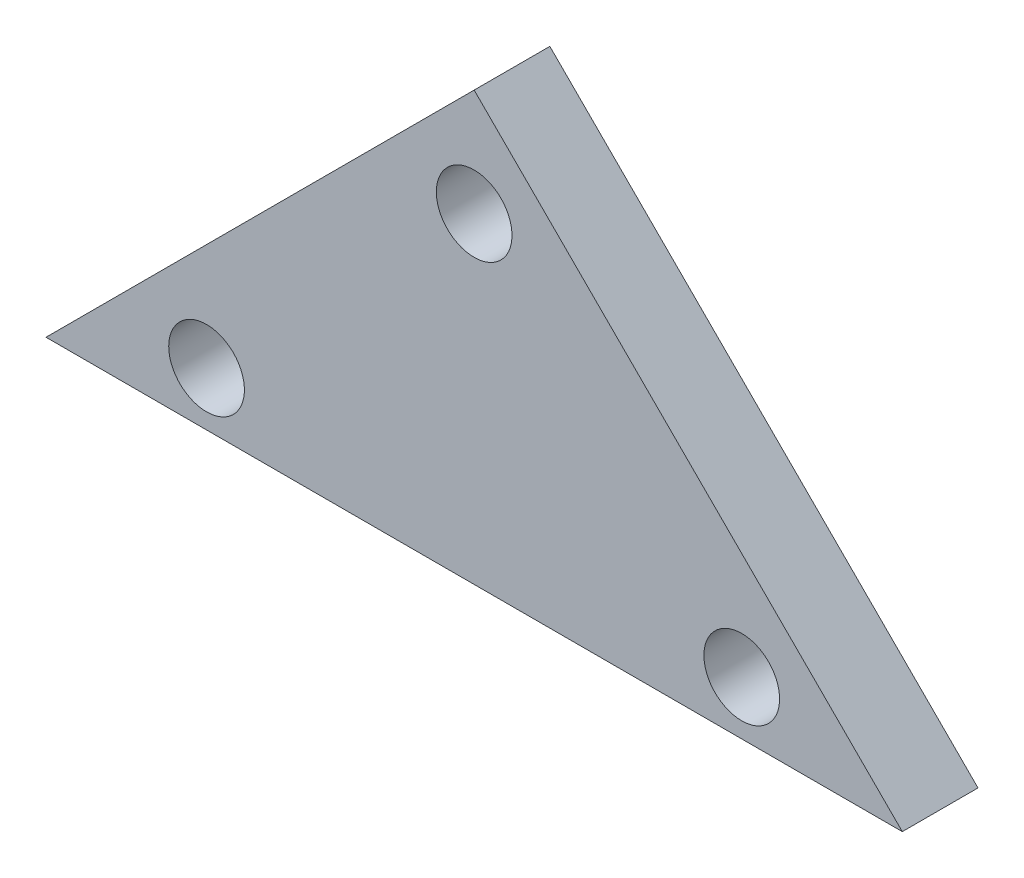
SolidWorks part; units mm, degrees
ref_plane "Front Plane" through (0, 0, 0) normal (0, 0, 1) x (1, 0, 0)
ref_plane "Top Plane" through (0, 0, 0) normal (0, 1, 0) x (1, 0, 0)
ref_plane "Right Plane" through (0, 0, 0) normal (1, 0, 0) x (0, 0, -1)
sketch "Sketch1" plane through (0, 0, 0) normal (0, 0, 1) x (1, 0, 0)
  line L0 (-26.9408, -20.2056) -> (26.9408, -20.2056)
  line L1 (26.9408, -20.2056) -> (0, 6.7352)
  line L2 (0, 6.7352) -> (-26.9408, -20.2056)
  line L3 (-13.4704, -6.7352) -> (13.4704, -6.7352) construction
  line L4 (0, 6.7352) -> (0, -6.7352) construction
  line L5 (0, -6.7352) -> (0, -20.2056) construction
  line L6 (-13.4704, -6.7352) -> (0, -20.2056) construction
  line L7 (0, -20.2056) -> (13.4704, -6.7352) construction
  line L8 (-26.9408, -20.2056) -> (-6.7352, -13.4704) construction
  line L9 (6.7352, -13.4704) -> (26.9408, -20.2056) construction
  circle A0 centre (0, 0) radius 2.3812
  circle A1 centre (-16.838, -16.838) radius 2.3813
  circle A2 centre (16.838, -16.838) radius 2.3813
  point P5 (0, 0)
  point P17 (0, 0)
  dimension "D1" = 4.7625
  dimension "D3" = 4.7625
  dimension "D4" = 4.7625
  dimension "D2" = 38.1
extrude "Boss-Extrude1" add sketch "Sketch1" along normal blind 4.7625
